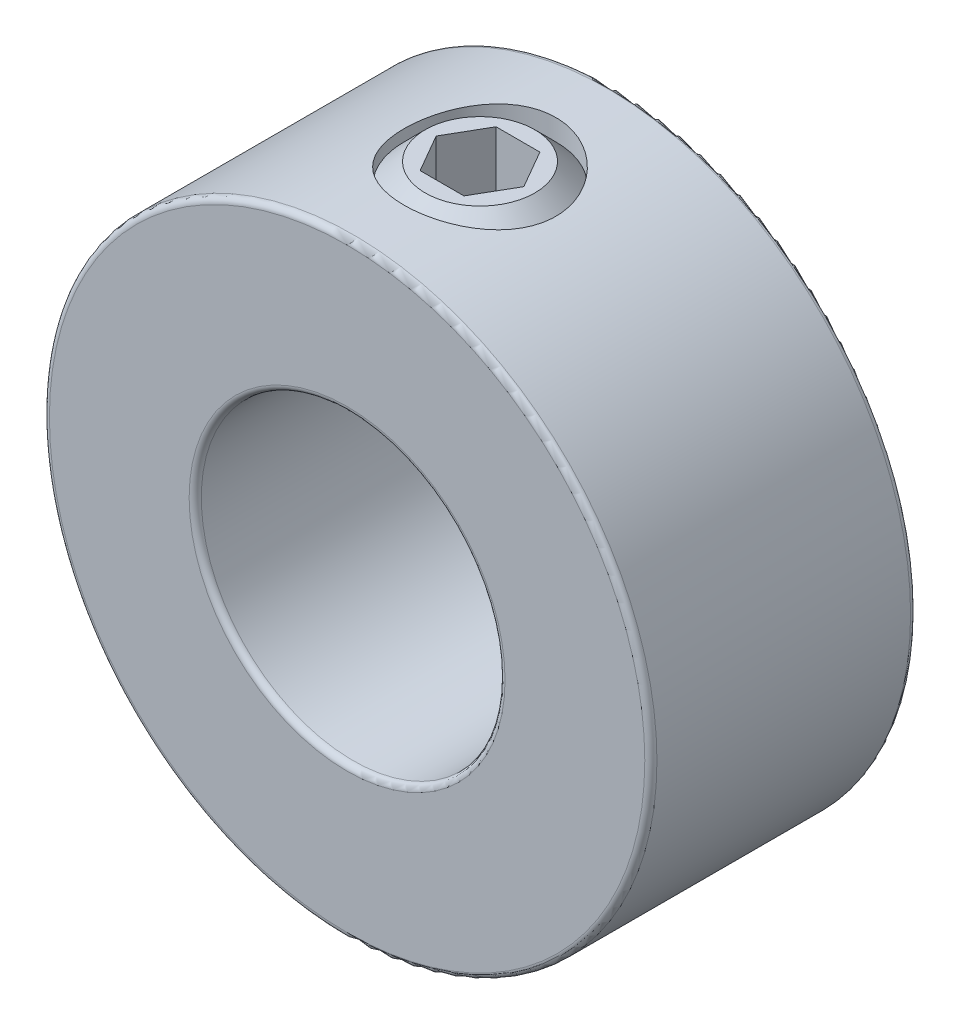
SolidWorks part; units mm, degrees
ref_plane "Front Plane" through (0, 0, 0) normal (0, 0, 1) x (1, 0, 0)
ref_plane "Top Plane" through (0, 0, 0) normal (0, 1, 0) x (1, 0, 0)
ref_plane "Right Plane" through (0, 0, 0) normal (1, 0, 0) x (0, 0, -1)
sketch "Sketch1" plane through (0, 0, 0) normal (0, 0, 1) x (1, 0, 0)
  circle A0 centre (0, 0) radius 12.7
  circle A1 centre (0, 0) radius 6.35
  point P4 (12.7, 0)
  point P5 (0, 12.7)
  dimension "Bore Dia" = 12.7
  dimension "OD" = 25.4
extrude "Extrude1" add sketch "Sketch1" along normal blind 11.1125
ref_plane "Plane1" through (0, 12.7, 0) normal (0, 1, 0) x (-1, 0, 0)
sketch "Sketch2" plane through (0, 12.7, 0) normal (0, 1, 0) x (-1, 0, 0)
  line L0 (0, 0) -> (0, 11.1125) construction
  line L2 (12.7, 11.1125) -> (-12.7, 11.1125) construction
  circle A0 centre (0, 5.5563) radius 3.175
  dimension "Set Screw Dia" = 6.35
extrude "Cut-Extrude1" cut sketch "Sketch2" against normal up to surface (12.7 mm away) up to plane "Top Plane"
ref_plane "Plane2" through (0, 0, 5.5563) normal (0, 0, 1) x (1, 0, 0)
sketch "Sketch3" plane through (0, 0, 5.5563) normal (0, 0, 1) x (1, 0, 0)
  line L0 (-2.2914, 12.7) -> (-3.175, 11.8164)
  line L1 (0, 7.7248) -> (0, 12.7)
  line L2 (-0.7937, 6.35) -> (-2.2914, 6.35)
  line L3 (-3.175, 7.2336) -> (-3.175, 11.8164)
  line L4 (0, 12.7) -> (-2.2914, 12.7)
  line L5 (0, 6.35) -> (0, 0) construction
  line L6 (-3.175, 11.8164) -> (0, 11.8164) construction
  line L7 (0, 7.7248) -> (-0.7937, 6.35)
  line L8 (-2.2914, 6.35) -> (-3.175, 7.2336)
  point P1 (-0.7937, 6.35)
  dimension "Screw Length" = 6.35
  dimension "D2" = 45
  dimension "D3" = 6.35
  dimension "D1" = 4.5827
  dimension "D4" = 60
  dimension "D5" = 45
  dimension "D7" = 3.175
  dimension "D8" = 0.7938
revolve "Revolve1" add sketch "Sketch3" angle 360 about L1
sketch "Sketch4" plane through (0, 12.7, 0) normal (0, 1, 0) x (0, 0, -1)
  line L0 (-5.5563, 1.8331) -> (-5.5563, -1.8331) construction
  line L1 (-5.5563, 1.8331) -> (-7.1438, 0.9165)
  line L2 (-7.1438, 0.9165) -> (-7.1438, -0.9165)
  line L3 (-7.1438, -0.9165) -> (-5.5563, -1.8331)
  line L4 (-5.5563, -1.8331) -> (-3.9688, -0.9165)
  line L5 (-3.9688, -0.9165) -> (-3.9688, 0.9165)
  line L6 (-3.9688, 0.9165) -> (-5.5563, 1.8331)
  circle A0 centre (-5.5563, 0) radius 1.5875 construction
  circle A1 centre (-5.5563, 0) radius 1.8331 construction
  dimension "D1" = 3.6662
  dimension "Hex" = 3.175
extrude "Cut-Extrude2" cut sketch "Sketch4" against normal blind 2.54
fillet "Fillet1" radius 0.254 4 edges at (6.35, 0, 0) (6.35, 0, 11.1125) (12.7, 0, 0) (12.7, 0, 11.1125)
equation "\"D3@Sketch3\" = \"Set Screw Dia@Sketch2\""
equation "\"D1@Fillet1\" = \"OD@Sketch1\"*.01"
equation "\"D1@Sketch3\" = \"D1@Sketch4\"*1.25"
equation "\"D1@Cut-Extrude2\" = \"Hex@Sketch4\"*.8"
equation "\"D8@Sketch3\" = \"D7@Sketch3\"/4"
